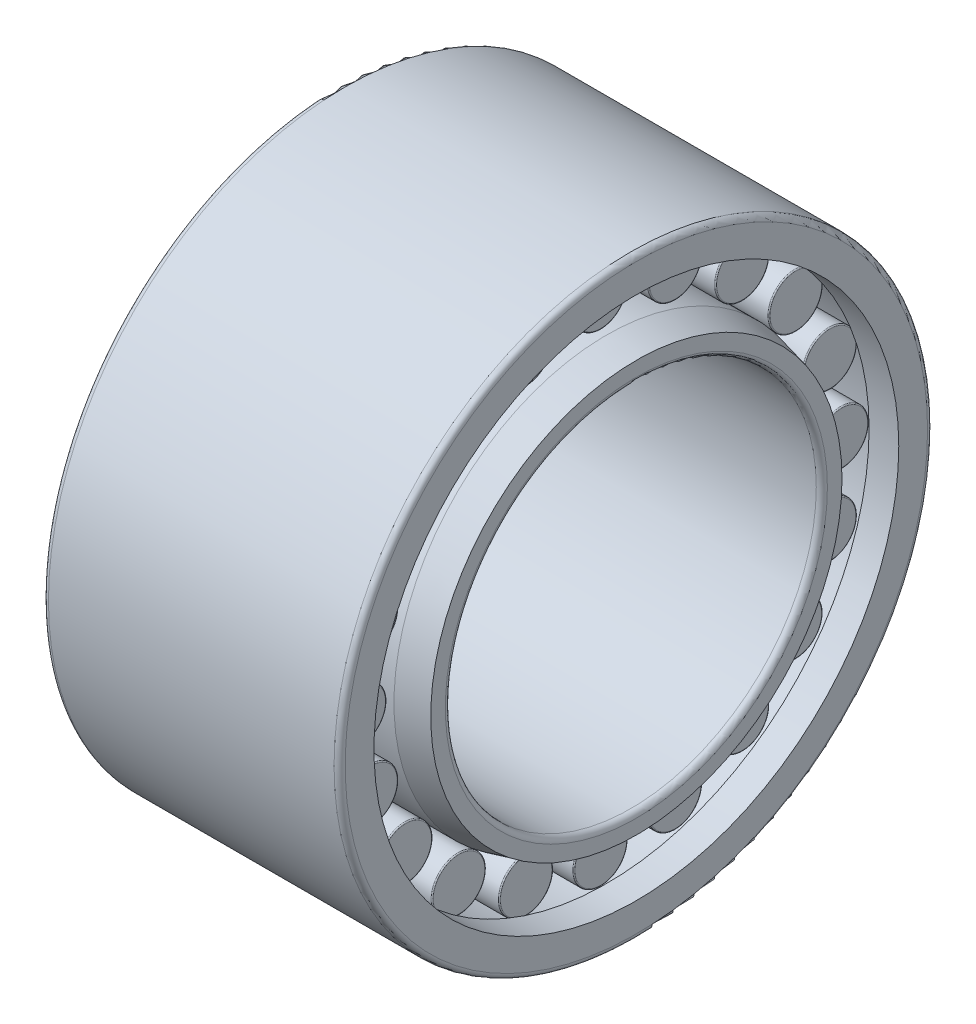
SolidWorks part; units mm, degrees
ref_plane "Plane1" through (0, 0, 0) normal (0, 0, 1) x (1, 0, 0)
ref_plane "Plane2" through (0, 0, 0) normal (0, 1, 0) x (1, 0, 0)
ref_plane "Plane3" through (0, 0, 0) normal (1, 0, 0) x (0, 0, -1)
other "Configuration Table"
sketch "Clipboard" plane through (0, 0, 0) normal (0, 0, 1) x (1, 0, 0)
  line L0 (-10, 0) -> (10, 0) construction
  line L1 (0, 0) -> (21.5565, -7.8459)
  line L2 (0, 0) -> (12.216, 4.4463)
  line L3 (0, 0) -> (27.3075, -9.9391)
  line L4 (0, 0) -> (-22.3573, -0.3902)
  dimension "CLdia" = 13
  dimension "Count" = 20
  dimension "Show_count" = 20
  dimension "Max_count" = 20
  dimension "Min_count" = 1
  dimension "Race_OD" = 29.06
  dimension "Race_ID" = 22.94
sketch "OutRacSke" plane through (0, 0, 0) normal (0, 0, 1) x (1, 0, 0)
  line L0 (-6.4, 14.1475) -> (-8, 14.1475)
  line L1 (-8, 14.1475) -> (-8, 15.7)
  line L2 (-7.7, 16) -> (7.7, 16)
  line L3 (8, 15.7) -> (8, 14.1475)
  line L4 (8, 14.1475) -> (6.4, 14.1475)
  line L5 (6.4, 14.1475) -> (6.4, 14.53)
  line L6 (6.4, 14.53) -> (-6.4, 14.53)
  line L7 (-6.4, 14.53) -> (-6.4, 14.1475)
  line L8 (-90, 0) -> (90, 0) construction
  arc A0 (-8, 15.7) -> (-7.7, 16) centre (-7.7, 15.7) cw
  arc A1 (7.7, 16) -> (8, 15.7) centre (7.7, 15.7) cw
  dimension "Race_OD" = 29.06
  dimension "radius" = 0.3
  dimension "OD" = 32
  dimension "Cyl_Len" = 12.8
  dimension "halfCylLen" = 6.4
  dimension "Width" = 16
  dimension "halfWidth" = 8
  dimension "groove_dp" = 0.3825
revolve "OuterRace" add sketch "OutRacSke" angle 360 about L8
sketch "RolDetSke" plane through (0, 0, 0) normal (0, 0, 1) x (1, 0, 0)
  line L0 (-6.08, 14.392) -> (-6.08, 13)
  line L1 (-6.08, 13) -> (6.08, 13)
  line L2 (6.08, 13) -> (6.08, 14.392)
  line L3 (6.022, 14.45) -> (-6.022, 14.45)
  line L4 (-33.6, 13) -> (33.6, 13) construction
  arc A0 (6.08, 14.392) -> (6.022, 14.45) centre (6.022, 14.392) ccw
  arc A1 (-6.022, 14.45) -> (-6.08, 14.392) centre (-6.022, 14.392) ccw
  dimension "radius" = 0.058
  dimension "RolCLRad" = 13
  dimension "Length" = 12.16
  dimension "halfLength" = 6.08
  dimension "Roller_diameter" = 2.9
revolve "RollerDetailed" add sketch "RolDetSke" angle 360 about L4
ref_axis "Axis1" through (-50, 0, 0) along (1, 0, 0)
sketch "RolSimSke" plane through (0, 101.6, 0) normal (0, 0, 1) x (1, 0, 0)
  line L0 (-6.08, -87.123) -> (-6.08, -90.077)
  line L1 (25.4, -101.6) -> (-25.4, -101.6) construction
  line L2 (6.08, -90.077) -> (6.08, -87.123)
  line L3 (6.022, -87.065) -> (-6.022, -87.065)
  line L5 (6.022, -90.135) -> (-6.022, -90.135)
  arc A0 (6.08, -87.123) -> (6.022, -87.065) centre (6.022, -87.123) ccw
  arc A1 (-6.022, -87.065) -> (-6.08, -87.123) centre (-6.022, -87.123) ccw
  arc A2 (6.08, -90.077) -> (6.022, -90.135) centre (6.022, -90.077) cw
  arc A3 (-6.022, -90.135) -> (-6.08, -90.077) centre (-6.022, -90.077) cw
  dimension "halfLength" = 6.08
  dimension "radius" = 0.058
  dimension "D1" = 11.465
  dimension "Roller_diameter" = 3.07
  dimension "Rol_Length" = 12.16
revolve "RollersSimplified" [suppressed] add sketch "RolSimSke" angle 360 about L1
sketch "InsRacSke" plane through (0, 0, 0) normal (0, 0, 1) x (1, 0, 0)
  line L0 (-6.4, 11.47) -> (-8, 11.0875)
  line L1 (-8, 11.0875) -> (-8, 10.3)
  line L2 (-7.7, 10) -> (7.7, 10)
  line L3 (8, 10.3) -> (8, 11.0875)
  line L4 (8, 11.0875) -> (6.4, 11.47)
  line L5 (6.4, 11.47) -> (-6.4, 11.47)
  line L6 (-90, 0) -> (90, 0) construction
  line L7 (0, 0) -> (0, 127) construction
  arc A0 (-8, 10.3) -> (-7.7, 10) centre (-7.7, 10.3) ccw
  arc A1 (7.7, 10) -> (8, 10.3) centre (7.7, 10.3) ccw
  dimension "Race_ID" = 22.94
  dimension "radius" = 0.3
  dimension "Cyl_Len" = 12.8
  dimension "Width" = 16
  dimension "groove_dp" = 0.3825
  dimension "Bore" = 20
revolve "InnerRace" add sketch "InsRacSke" angle 360 about L6
pattern_circular "RollersDetailed" count 20 every 18 about axis through (-50, 0, 0) along (1, 0, 0) of "RollerDetailed"
sketch "CagSpiSke" plane through (0, 0, 0) normal (0, 0, 1) x (1, 0, 0)
  line L0 (7.2, 12.6375) -> (7.2, 13.3625)
  line L1 (7.2, 13.3625) -> (-7.2, 13.3625)
  line L2 (-7.2, 13.3625) -> (-7.2, 12.6375)
  line L3 (-7.2, 12.6375) -> (7.2, 12.6375)
  line L4 (-90, 0) -> (90, 0) construction
  dimension "Cag_IR" = 25.275
  dimension "thickness" = 0.725
  dimension "width" = 14.4
  dimension "halfwidth" = 7.2
revolve "CageSpine" [suppressed] add sketch "CagSpiSke" angle 0.001 about L4
equation "\"CLdia@Clipboard\" =  ( \"Race_OD@Clipboard\" + \"Race_ID@Clipboard\" )  / 4"
equation "\"Race_OD@OutRacSke\" = \"Race_OD@Clipboard\""
equation "\"halfCylLen@OutRacSke\" = \"Cyl_Len@OutRacSke\" / 2"
equation "\"RolCLRad@RolDetSke\" = \"CLdia@Clipboard\""
equation "\"Roller_diameter@RolSimSke\" =  ( \"Race_OD@Clipboard\" - \"Race_ID@Clipboard\" )  / 2 + .01"
equation "\"radius@RolDetSke\" = \"Roller_diameter@RolDetSke\" / 50"
equation "\"Length@RolDetSke\" = \"Cyl_Len@OutRacSke\" * .95"
equation "\"halfLength@RolDetSke\" = \"Length@RolDetSke\" / 2"
equation "\"thickness@CagSpiSke\"  = \"Roller_diameter@RolDetSke\" * 0.25"
equation "\"Cag_IR@CagSpiSke\" =  \"RolCLRad@RolDetSke\" * 2 - \"thickness@CagSpiSke\""
equation "\"Rol_Length@RolSimSke\" = \"Cyl_Len@OutRacSke\" * .95"
equation "\"halfLength@RolSimSke\" = \"Rol_Length@RolSimSke\" / 2"
equation "\"radius@RolSimSke\" = \"radius@RolDetSke\""
equation "\"D1@RolSimSke\" = \"CLdia@Clipboard\" -  ( \"Roller_diameter@RolSimSke\" / 2 ) "
equation "\"Max_count@Clipboard\" = int( 3.14159265 / atn(( \"Roller_diameter@RolDetSke\" / 2) / sqr( \"RolCLRad@RolDetSke\"  *  \"RolCLRad@RolDetSke\" - ( \"Roller_diameter@RolDetSke\" / 2) *  ( \"Roller_diameter@RolDetSke\" / 2))))"
equation "\"Max_count@Clipboard\" = ((sgn( \"Max_count@Clipboard\" - \"Count@Clipboard\" )-1)*( \"Max_count@Clipboard\" - \"Count@Clipboard\" ))/-2+ \"Count@Clipboard\""
equation "\"Count@RollersDetailed\"=int( \"Show_count@Clipboard\" )"
equation "\"Count@RollersDetailed\" = ((sgn( \"Count@RollersDetailed\" - \"Max_count@Clipboard\" )-1)*( \"Count@RollersDetailed\" - \"Max_count@Clipboard\" ))/-2+ \"Max_count@Clipboard\""
equation "\"Angle@RollersDetailed\" = 360.0 / \"Max_count@Clipboard\""
equation "\"halfWidth@OutRacSke\" = \"Width@OutRacSke\" / 2"
equation "\"radius@InsRacSke\" = \"radius@OutRacSke\" "
equation "\"groove_dp@InsRacSke\" = \"groove_dp@OutRacSke\""
equation "\"Width@InsRacSke\" = \"Width@OutRacSke\""
equation "' \"halfWidth@InsRacSke\" = \"Width@OutRacSke\" / 2"
equation "\"Race_ID@InsRacSke\" = \"Race_ID@Clipboard\""
equation "\"Cyl_Len@InsRacSke\" = \"Cyl_Len@OutRacSke\""
equation "\"Angle@CageSpine\" =  \"Angle@RollersDetailed\" * ( \"Count@RollersDetailed\" -1 + int( \"Count@RollersDetailed\" / \"Max_count@Clipboard\" ) )  + 0.001 -  int( \"Count@RollersDetailed\" / \"Max_count@Clipboard\" ) * 0.001"
equation "\"Angle@CageSpine\" =  \"Angle@CageSpine\" * int( \"Min_count@Clipboard\" / 2) + int(1 / \"Min_count@Clipboard\")  * 0.001"
equation "\"width@CagSpiSke\" =   ( \"Width@InsRacSke\" + \"Cyl_Len@InsRacSke\" )  / 2"
equation "\"halfwidth@CagSpiSke\" = \"width@CagSpiSke\" / 2"
